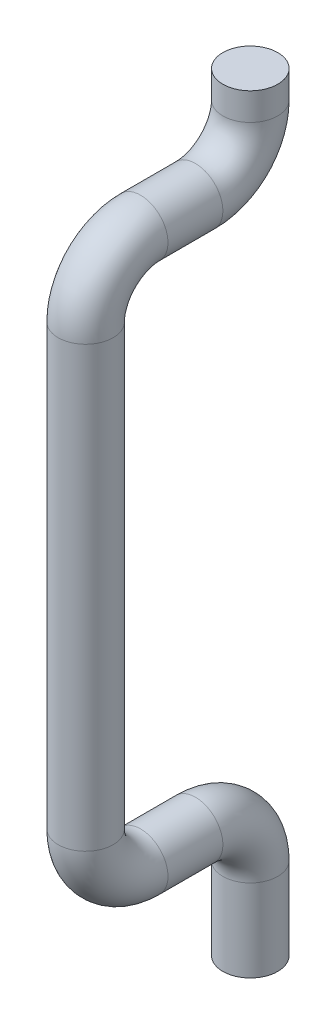
SolidWorks part; units mm, degrees
material "1023 Carbon Steel Sheet (SS)"
ref_plane "Front Plane" through (0, 0, 0) normal (0, 0, 1) x (1, 0, 0)
ref_plane "Top Plane" through (0, 0, 0) normal (0, 1, 0) x (1, 0, 0)
ref_plane "Right Plane" through (0, 0, 0) normal (1, 0, 0) x (0, 0, -1)
sketch "Sketch1" plane through (0, 0, 0) normal (1, 0, 0) x (0, 0, -1)
  line L0 (11.22, 3) -> (13.22, 3)
  line L1 (15.22, 1) -> (15.22, -2)
  line L2 (9.22, 5) -> (9.22, 21)
  line L3 (11.22, 23) -> (13.22, 23)
  line L4 (15.22, 25) -> (15.22, 26)
  arc A0 (13.22, 3) -> (15.22, 1) centre (13.22, 1) cw
  arc A1 (9.22, 5) -> (11.22, 3) centre (11.22, 5) ccw
  arc A3 (9.22, 21) -> (11.22, 23) centre (11.22, 21) cw
  arc A4 (13.22, 23) -> (15.22, 25) centre (13.22, 25) ccw
  point P9 (15.22, 3)
  point P19 (9.22, 23)
  point P22 (15.22, 23)
  dimension "D8" = 2
  dimension "D9" = 2
  dimension "D5" = 2
  dimension "D1" = 3
  dimension "D2" = 6
  dimension "D3" = 20
  dimension "D4" = 5
ref_plane "Plane1" through (0, -2, 0) normal (0, 1, 0) x (1, 0, 0)
sketch "Sketch2" plane through (0, -2, 0) normal (0, 1, 0) x (1, 0, 0)
  circle A0 centre (0, 15.22) radius 1
  dimension "D1" = 2
sweep "Sweep1" add profiles "Sketch2" path "Sketch1"
